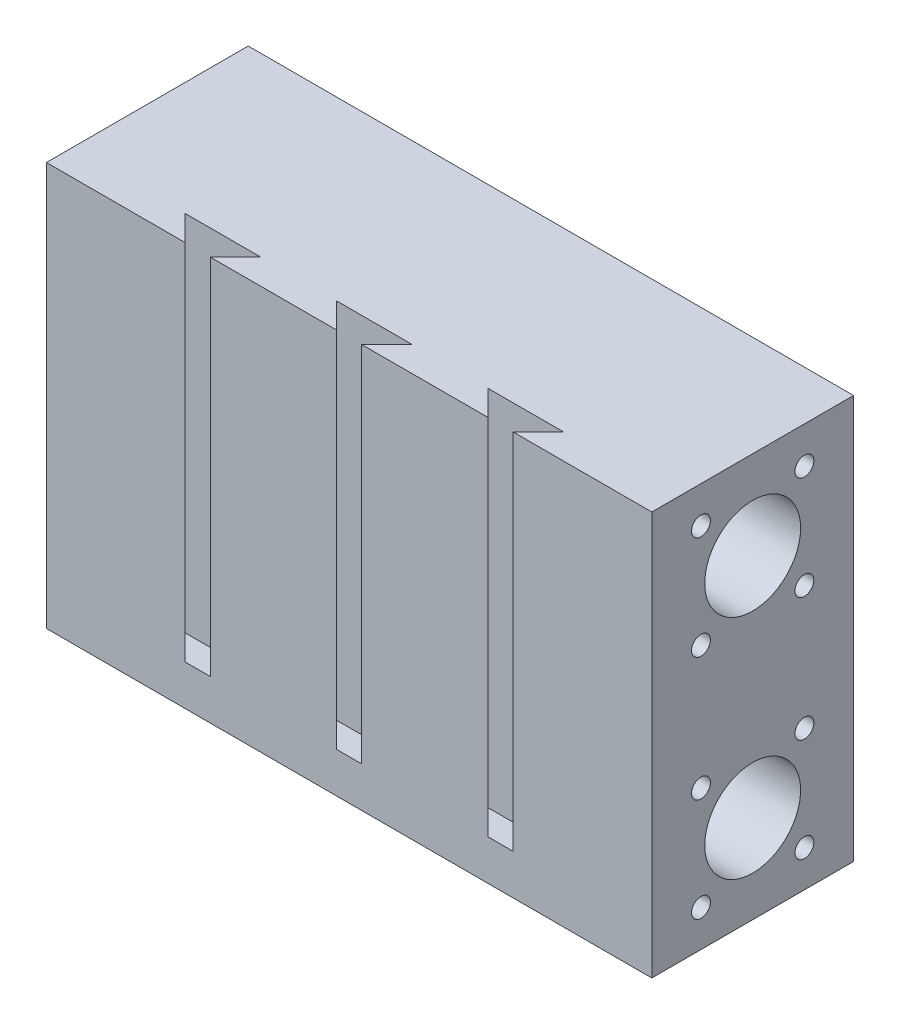
SolidWorks part; units mm, degrees
ref_plane "Front Plane" through (0, 0, 0) normal (0, 0, 1) x (1, 0, 0)
ref_plane "Top Plane" through (0, 0, 0) normal (0, 1, 0) x (1, 0, 0)
ref_plane "Right Plane" through (0, 0, 0) normal (1, 0, 0) x (0, 0, -1)
sketch "Sketch1" plane through (0, 0, 0) normal (0, 0, 1) x (1, 0, 0)
  line L1 (0, 0) -> (120, 0)
  line L2 (0, 0) -> (0, 80)
  line L3 (0, 80) -> (120, 80)
  line L4 (120, 0) -> (120, 80)
  dimension "D1" = 80
  dimension "D2" = 120
extrude "Boss-Extrude1" add sketch "Sketch1" along normal blind 40 contours L3 L4 L1 L2
sketch "Sketch2" plane through (0, 0, 0) normal (-1, 0, 0) x (0, 0, 1)
  line L0 (20, 80) -> (20, 0) construction
  line L1 (40, 80) -> (0, 80) construction
  line L2 (40, 0) -> (0, 0) construction
  line L3 (40, 40) -> (0, 40) construction
  line L4 (40, 0) -> (40, 80) construction
  line L5 (0, 0) -> (0, 80) construction
  line L6 (0, 62.5) -> (40, 62.5) construction
  line L7 (0, 17.5) -> (40, 17.5) construction
  circle A1 centre (30.25, 72.75) radius 1.85
  circle A2 centre (9.75, 72.75) radius 1.85
  circle A3 centre (30.25, 52.25) radius 1.85
  circle A4 centre (9.75, 52.25) radius 1.85
  circle A5 centre (9.75, 27.75) radius 1.85
  circle A6 centre (30.25, 27.75) radius 1.85
  circle A7 centre (30.25, 7.25) radius 1.85
  circle A9 centre (9.75, 7.25) radius 1.85
  dimension "D4" = 3.7
  dimension "D1" = 22.5
  dimension "D2" = 9.75
  dimension "D3" = 7.25
extrude "linear-bearing-screw-cuts" cut sketch "Sketch2" against normal blind 14
sketch "Sketch3" plane through (0, 0, 0) normal (-1, 0, 0) x (0, 0, 1)
  line L0 (20, 80) -> (20, 0) construction
  line L1 (40, 80) -> (0, 80) construction
  line L2 (40, 0) -> (0, 0) construction
  line L3 (0, 40) -> (40, 40) construction
  line L4 (0, 0) -> (0, 80) construction
  line L5 (40, 0) -> (40, 80) construction
  line L6 (0, 62.5) -> (40, 62.5) construction
  line L7 (0, 17.5) -> (40, 17.5) construction
  circle A0 centre (20, 62.5) radius 9.5
  circle A2 centre (20, 17.5) radius 9.5
  dimension "D2" = 19
  dimension "D1" = 45
extrude "linear-bearings-hole" cut sketch "Sketch3" against normal blind 55
sketch "Sketch4" plane through (120, 0, 0) normal (1, 0, 0) x (0, 0, -1)
  line L0 (-20, 80) -> (-20, 0) construction
  line L1 (-40, 80) -> (0, 80) construction
  line L2 (-40, 0) -> (0, 0) construction
  line L3 (-40, 40) -> (0, 40) construction
  line L4 (-40, 0) -> (-40, 80) construction
  line L5 (0, 0) -> (0, 80) construction
  line L6 (-40, 62.5) -> (0, 62.5) construction
  line L7 (-40, 17.5) -> (0, 17.5) construction
  circle A0 centre (-9.75, 72.75) radius 1.875
  circle A1 centre (-30.25, 72.75) radius 1.875
  circle A2 centre (-9.75, 52.25) radius 1.875
  circle A3 centre (-30.25, 52.25) radius 1.875
  circle A4 centre (-30.25, 27.75) radius 1.875
  circle A5 centre (-9.75, 27.75) radius 1.875
  circle A6 centre (-9.75, 7.25) radius 1.875
  circle A7 centre (-30.25, 7.25) radius 1.875
  dimension "D2" = 3.75
  dimension "D1" = 45
  dimension "D3" = 7.25
  dimension "D4" = 9.75
extrude "linear-bearing-screw-cuts2" cut sketch "Sketch4" against normal blind 14
sketch "Sketch5" plane through (120, 0, 0) normal (1, 0, 0) x (0, 0, -1)
  line L0 (-20, 80) -> (-20, 0) construction
  line L1 (-40, 80) -> (0, 80) construction
  line L2 (-40, 0) -> (0, 0) construction
  line L3 (0, 40) -> (-40, 40) construction
  line L4 (0, 0) -> (0, 80) construction
  line L5 (-40, 0) -> (-40, 80) construction
  line L6 (-40, 62.5) -> (0, 62.5) construction
  line L7 (-40, 17.5) -> (0, 17.5) construction
  circle A0 centre (-20, 62.5) radius 9.5
  circle A1 centre (-20, 17.5) radius 9.5
  dimension "D2" = 19
  dimension "D1" = 45
extrude "linear-bearings-hole2" cut sketch "Sketch5" against normal blind 55
sketch "Sketch10" plane through (0, 80, 0) normal (0, 1, 0) x (1, 0, 0)
  line L0 (60, 0) -> (60, -40) construction
  line L1 (0, 0) -> (120, 0) construction
  line L2 (0, -40) -> (120, -40) construction
  line L3 (75, 0) -> (75, -40) construction
  line L4 (92.5, -40) -> (97.5, -35)
  line L5 (97.5, -35) -> (82.5, -35)
  line L6 (82.5, -35) -> (87.5, -40)
  line L7 (87.5, -40) -> (92.5, -40)
  line L8 (120, -40) -> (120, 0) construction
  line L9 (67.5, -35) -> (62.5, -40)
  line L10 (52.5, -35) -> (67.5, -35)
  line L11 (57.5, -40) -> (52.5, -35)
  line L12 (62.5, -40) -> (57.5, -40)
  line L13 (37.5, -35) -> (32.5, -40)
  line L14 (22.5, -35) -> (37.5, -35)
  line L15 (27.5, -40) -> (22.5, -35)
  line L16 (32.5, -40) -> (27.5, -40)
  point P10 (90, -40)
  dimension "D1" = 45
  dimension "D2" = 15
  dimension "D3" = 5
  dimension "D4" = 30
  dimension "D5" = 45
extrude "Cut-Extrude7" cut sketch "Sketch10" against normal blind 72
sketch "Sketch11" plane through (0, 0, 40) normal (0, 0, 1) x (1, 0, 0)
  line L0 (0, 0) -> (120, 0) construction
  line L1 (0, 0) -> (0, 80) construction
  circle A0 centre (13.5, 35) radius 1.25
  circle A1 centre (44.5, 35) radius 1.25
  circle A2 centre (75.5, 35) radius 1.25
  circle A3 centre (106.5, 35) radius 1.25
  circle A4 centre (13.5, 4) radius 1.25
  circle A5 centre (44.5, 4) radius 1.25
  circle A6 centre (75.5, 4) radius 1.25
  circle A7 centre (106.5, 4) radius 1.25
  dimension "D7" = 2.5
  dimension "D1" = 4
  dimension "D2" = 31
  dimension "D3" = 31
  dimension "D4" = 31
  dimension "D5" = 31
  dimension "D6" = 13.5
extrude "Cut-Extrude8" [suppressed] cut sketch "Sketch11" against normal through all
